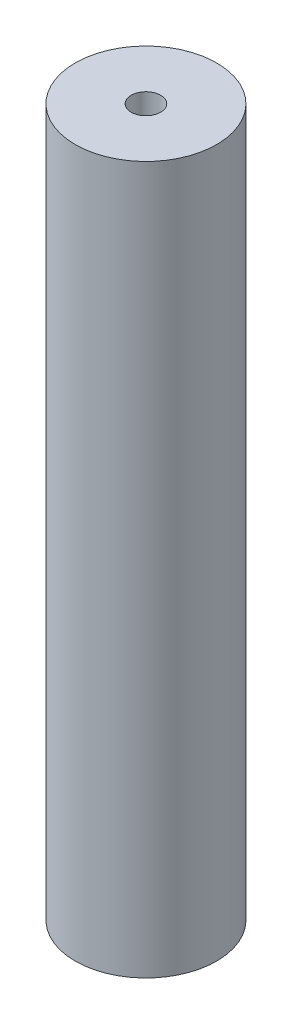
SolidWorks part; units mm, degrees
material "6061-T6 (SS)"
ref_plane "Front Plane" through (0, 0, 0) normal (0, 0, 1) x (1, 0, 0)
ref_plane "Top Plane" through (0, 0, 0) normal (0, 1, 0) x (1, 0, 0)
ref_plane "Right Plane" through (0, 0, 0) normal (1, 0, 0) x (0, 0, -1)
sketch "Sketch1" plane through (0, 0, 0) normal (0, 1, 0) x (1, 0, 0)
  circle A0 centre (0, 0) radius 6
  dimension "D1" = 12
extrude "Boss-Extrude1" add sketch "Sketch1" along normal blind 60
sketch "Sketch4" plane through (0, 60, 0) normal (0, 1, 0) x (1, 0, 0)
  point P0 (0, 0)
hole_wizard "Tap Drill for M3 Tap1" positions "Sketch4" profile "Sketch3" hole size "M3" standard "DIN" end condition through all
sketch "Sketch3" plane through (0, 60, 0) normal (1, 0, 0) x (0, 0, 1)
  line L0 (0, 0) -> (0, 60)
  line L1 (0, 60) -> (1.25, 60)
  line L2 (1.25, 60) -> (1.25, 0)
  line L5 (1.25, 0) -> (0, 0)
  line L11 (0, -6.35) -> (0, 107.95) construction
  dimension "Thru Hole Dia." = 2.5
  dimension "Thru Hole Depth" = 60
